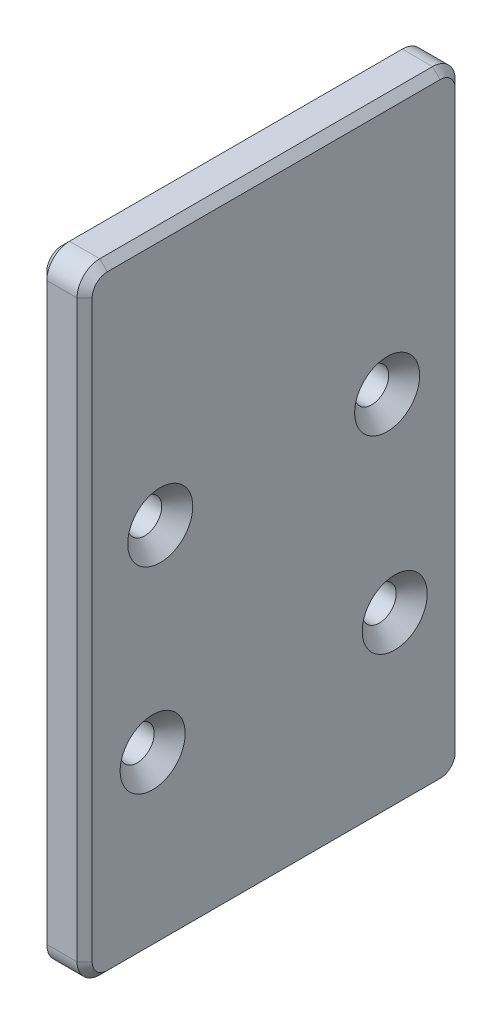
SolidWorks part; units mm, degrees
ref_plane "前视基准面" through (0, 0, 0) normal (0, 0, 1) x (1, 0, 0)
ref_plane "上视基准面" through (0, 0, 0) normal (0, 1, 0) x (1, 0, 0)
ref_plane "右视基准面" through (0, 0, 0) normal (1, 0, 0) x (0, 0, -1)
other "Configuration Table"
sketch "草图1" plane through (0, 0, 0) normal (1, 0, 0) x (0, 0, -1)
  line L1 (-25, -41) -> (25, -41)
  line L2 (-25, -41) -> (-25, 41)
  line L3 (-25, 41) -> (25, 41)
  line L4 (25, -41) -> (25, 41)
  line L5 (-25, -41) -> (25, 41) construction
  line L6 (-25, 41) -> (25, -41) construction
  point P0 (0, 0)
  dimension "D1" = 50
  dimension "D2" = 82
extrude "凸台-拉伸1" add sketch "草图1" along normal blind 6
fillet "圆角1" radius 3 4 edges at (3, -41, 25) (3, -41, -25) (3, 41, 25) (3, 41, -25)
chamfer "倒角1" distance 1 angle 45 16 edges at (0, -40.1213, -24.1213) (0, 0, -25) (0, 40.1213, -24.1213) (0, 41, 0) (0, 40.1213, 24.1213) (0, 0, 25) (0, -40.1213, 24.1213) (0, -41, 0) (6, 40.1213, 24.1213) (6, 41, 0) (6, 40.1213, -24.1213) (6, 0, -25) (6, -40.1213, -24.1213) (6, -41, 0) (6, -40.1213, 24.1213) (6, 0, 25)
hole_wizard "M4 十字槽沉头木螺钉的锥形沉头孔1" positions "草图7" profile "草图6" countersink size "M4" standard "GB" end condition through all
sketch "草图7" plane through (6, 0, 0) normal (1, 0, 0) x (0, 0, -1)
  point P0 (15, 7.5)
  point P3 (-15, 7.5)
  point P6 (16, -18)
  point P9 (-16, -18)
sketch "草图6" plane through (6, 7.5, -15) normal (0, 1, 0) x (0, 0, -1)
  line L0 (0, 0) -> (0, 6)
  line L1 (0, 6) -> (2.25, 6)
  line L2 (2.25, 6) -> (2.25, 2.05)
  line L3 (2.25, 2.05) -> (4.3, 0)
  line L5 (4.3, 0) -> (0, 0)
  line L6 (-2.25, 2.05) -> (-4.3, 0) construction
  line L11 (0, -6.35) -> (0, 107.95) construction
  dimension "通孔孔直径" = 4.5
  dimension "通孔孔深度" = 6
  dimension "近端锥形沉头孔直径" = 8.6
  dimension "近端锥形沉头孔角度" = 90
